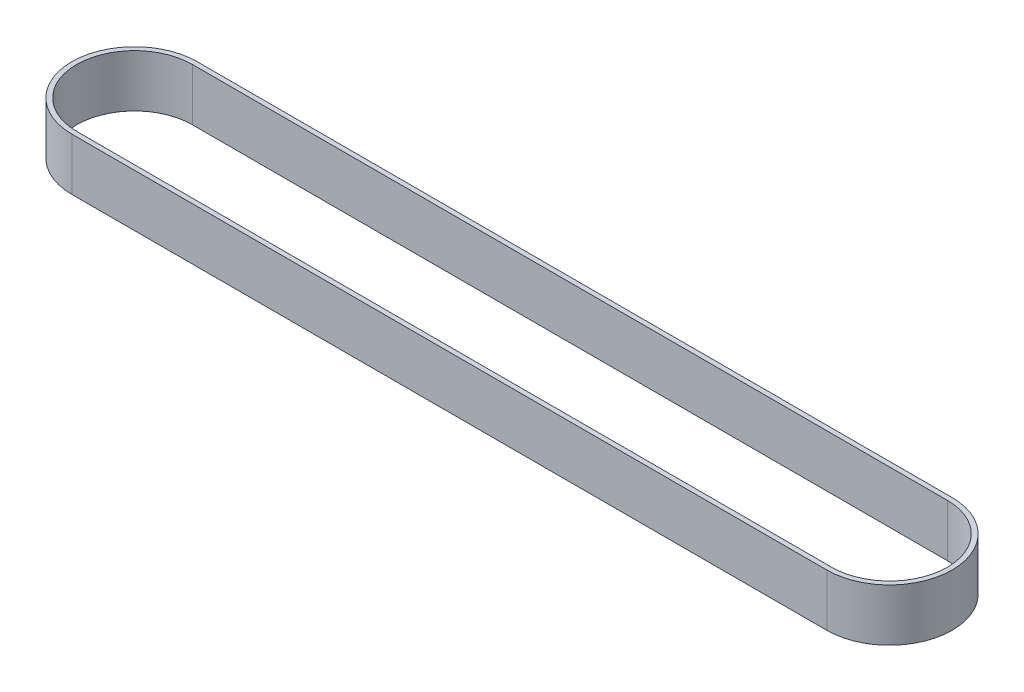
SolidWorks part; units mm, degrees
material "EPDM 60 硬度计"
ref_plane "前视基准面" through (0, 0, 0) normal (0, 0, 1) x (1, 0, 0)
ref_plane "上视基准面" through (0, 0, 0) normal (0, 1, 0) x (1, 0, 0)
ref_plane "右视基准面" through (0, 0, 0) normal (1, 0, 0) x (0, 0, -1)
sketch "草图1" plane through (0, 0, 0) normal (0, 1, 0) x (1, 0, 0)
  line L1 (0, 11.08) -> (144.5, 11.08)
  line L2 (0, 11.08) -> (0, -11.08)
  line L3 (0, -11.08) -> (144.5, -11.08)
  line L4 (144.5, 11.08) -> (144.5, -11.08)
  line L5 (0, 12) -> (144.5, 12)
  line L6 (0, 12) -> (0, -12)
  line L7 (0, -12) -> (144.5, -12)
  line L8 (144.5, 12) -> (144.5, -12)
  circle A0 centre (0, 0) radius 11.08
  circle A1 centre (144.5, 0) radius 11.08
  circle A2 centre (0, 0) radius 12
  circle A3 centre (144.5, 0) radius 12
  dimension "D1" = 22.16
  dimension "D3" = 24
  dimension "D2" = 144.5
  dimension "D4" = 144.5
extrude "凸台-拉伸1" add sketch "草图1" along normal blind 10 contours L8 A3 A1 | L8 A3 L1 | A3 L5 A2 L1 | L3 A3 L8 | A3 L3 A2 L7 | L1 A2 L6 | L6 A2 L3 | L6 A2 A0
